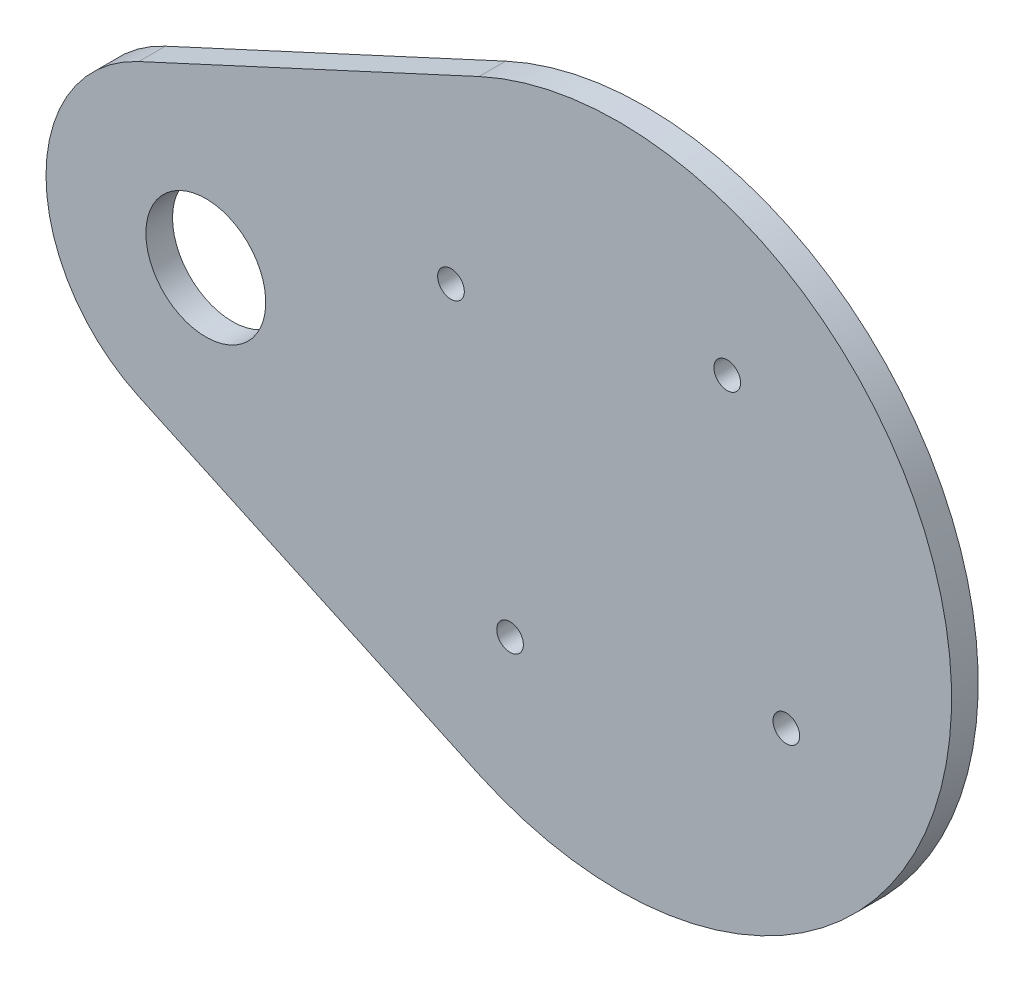
SolidWorks part; units mm, degrees
ref_plane "Front Plane" through (0, 0, 0) normal (0, 0, 1) x (1, 0, 0)
ref_plane "Top Plane" through (0, 0, 0) normal (0, 1, 0) x (1, 0, 0)
ref_plane "Right Plane" through (0, 0, 0) normal (1, 0, 0) x (0, 0, -1)
sketch "Sketch1" plane through (0, 0, 0) normal (0, 0, 1) x (1, 0, 0)
  line L8 (-55.4014, 4.3896) -> (-55.4014, -4.3896)
  line L9 (-46.0323, -10.8939) -> (-36.0323, -10.8939)
  line L10 (-36.0323, -10.8939) -> (-10.4839, -22.6956)
  line L11 (22.5016, -10.8939) -> (32.5016, -10.8939)
  line L12 (41.8707, -4.3896) -> (41.8707, 4.3896)
  line L13 (32.5016, 10.8939) -> (22.5016, 10.8939)
  line L14 (-10.4839, 22.6956) -> (-36.0323, 10.8939)
  line L15 (-36.0323, 10.8939) -> (-46.0323, 10.8939)
  line L18 (-36.0323, -10.8939) -> (-10.4839, -22.6956)
  line L19 (22.5016, -10.8939) -> (32.5016, -10.8939)
  line L22 (-10.4839, 22.6956) -> (-36.0323, 10.8939)
  circle A0 centre (12.59, -8.1543) radius 1 construction
  circle A1 centre (8.1543, 12.59) radius 1 construction
  circle A2 centre (-12.59, 8.1543) radius 1 construction
  circle A3 centre (-8.1543, -12.59) radius 1 construction
  circle A4 centre (12.59, -8.1543) radius 1
  circle A5 centre (8.1543, 12.59) radius 1
  arc A6 (-46.0323, 10.8939) -> (-55.4014, 4.3896) centre (-46.0323, 0.8939) ccw
  arc A7 (-55.4014, -4.3896) -> (-46.0323, -10.8939) centre (-46.0323, -0.8939) ccw
  arc A8 (-10.4839, -22.6956) -> (22.5016, -10.8939) centre (0, 0) ccw
  arc A9 (32.5016, -10.8939) -> (41.8707, -4.3896) centre (32.5016, -0.8939) ccw
  arc A10 (41.8707, 4.3896) -> (32.5016, 10.8939) centre (32.5016, 0.8939) ccw
  arc A11 (22.5016, 10.8939) -> (-10.4839, 22.6956) centre (0, 0) ccw
  arc A14 (-10.4839, -22.6956) -> (22.5016, -10.8939) centre (0, 0) ccw
  arc A17 (22.5016, 10.8939) -> (-10.4839, 22.6956) centre (0, 0) ccw
  circle A18 centre (-12.59, 8.1543) radius 1
  circle A19 centre (-8.1543, -12.59) radius 1
  circle A23 centre (-31, 0) radius 7.5 construction
  circle A24 centre (-31, 0) radius 7.5 construction
  arc A34 (22.5016, 10.8939) -> (22.5016, -10.8939) centre (0, 0) cw
  arc A35 (-36.0323, 10.8939) -> (-36.0323, -10.8939) centre (-31, 0) ccw
  arc A36 (-26.8019, -1.6206) -> (-35.1981, 1.6206) centre (-31, 0) ccw construction
  arc A37 (-26.8019, -1.6206) -> (-35.1981, 1.6206) centre (-31, 0) ccw
  arc A38 (-35.1981, 1.6206) -> (-26.8019, -1.6206) centre (-31, 0) ccw
  dimension "D1" = 0
extrude "Boss-Extrude1" add sketch "Sketch1" along normal up to surface (2 mm away)
